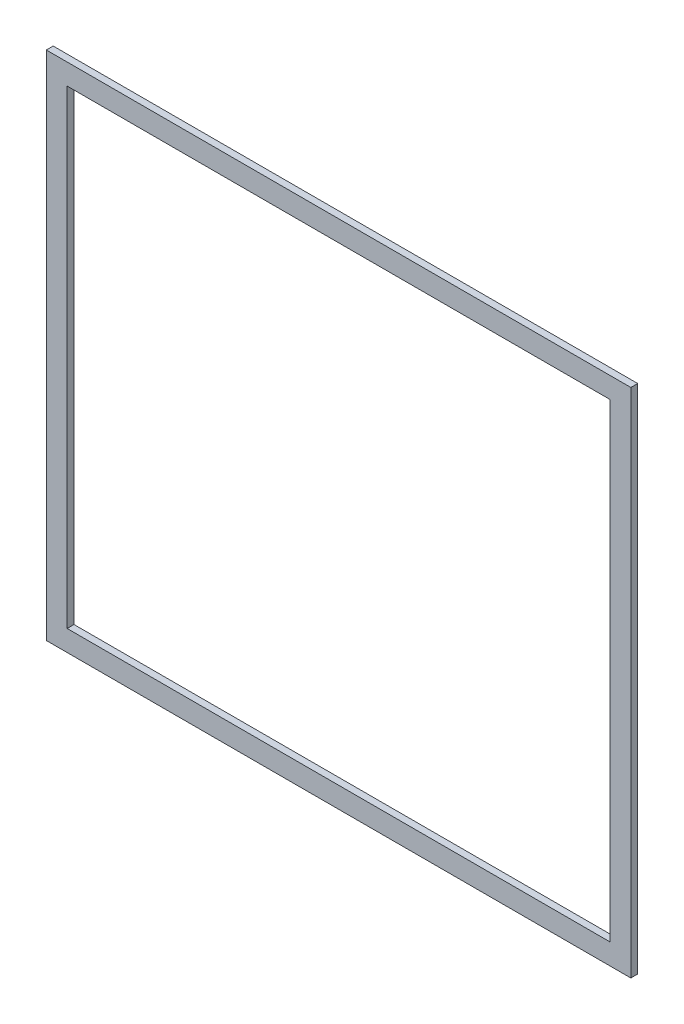
SolidWorks part; units mm, degrees
ref_plane "Front Plane" through (0, 0, 0) normal (0, 0, 1) x (1, 0, 0)
ref_plane "Top Plane" through (0, 0, 0) normal (0, 1, 0) x (1, 0, 0)
ref_plane "Right Plane" through (0, 0, 0) normal (1, 0, 0) x (0, 0, -1)
sketch "Sketch1" plane through (0, 0, 0) normal (0, 0, 1) x (1, 0, 0)
  line L0 (-97.917, 85.217) -> (97.917, 85.217)
  line L1 (97.917, 85.217) -> (97.917, -85.217)
  line L2 (97.917, -85.217) -> (-97.917, -85.217)
  line L3 (-97.917, -85.217) -> (-97.917, 85.217)
  point P3 (0, 85.217)
  point P5 (97.917, 0)
  dimension "D1" = 170.434
  dimension "D2" = 195.834
sketch "Sketch2" plane through (0, 0, 0) normal (1, 0, 0) x (0, 0, -1)
  line L0 (0, 88.8365) -> (0, 81.5975)
  line L1 (0, 81.5975) -> (-2.3876, 81.5975)
  line L2 (-2.3876, 81.5975) -> (-2.3876, 88.8365)
  line L3 (-2.3876, 88.8365) -> (0, 88.8365)
  dimension "D1" = 7.239
  dimension "D2" = 2.3876
sweep "Sweep1" add profiles "Sketch2" path "Sketch1"
